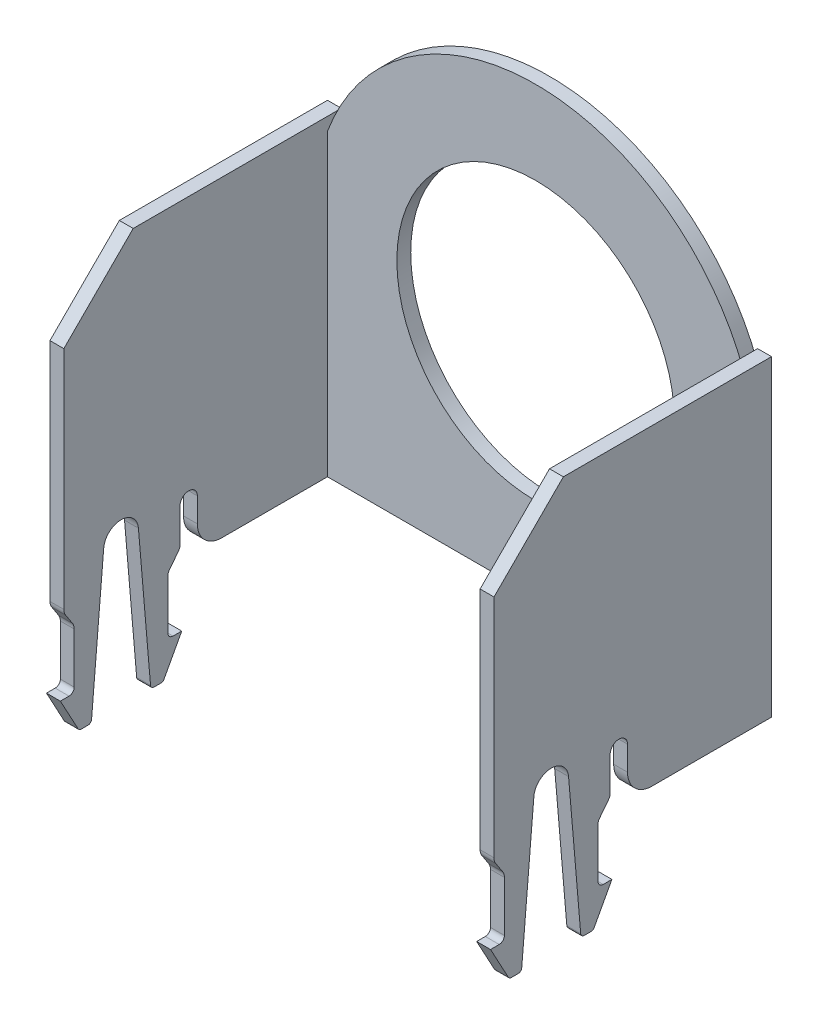
SolidWorks part; units mm, degrees
ref_plane "Płaszczyzna przednia" through (0, 0, 0) normal (0, 0, 1) x (1, 0, 0)
ref_plane "Płaszczyzna górna" through (0, 0, 0) normal (0, 1, 0) x (1, 0, 0)
ref_plane "Płaszczyzna prawa" through (0, 0, 0) normal (1, 0, 0) x (0, 0, -1)
sketch "Szkic1" plane through (0, 0, 0) normal (0, 0, 1) x (1, 0, 0)
  line L0 (0, -6.4) -> (6.4, -6.4)
  line L1 (6.4, -6.4) -> (6.4, 0)
  line L2 (-6.4, 0) -> (-6.4, -6.4)
  line L3 (-6.4, -6.4) -> (0, -6.4)
  arc A0 (6.4, 0) -> (-6.4, 0) centre (0, 0) ccw
  dimension "D1" = 12.8
extrude "Dodanie-wyciągnięcie1" add sketch "Szkic1" along normal blind 0.4
sketch "Szkic6" plane through (0, 0, 0.4) normal (0, 0, 1) x (1, 0, 0)
  circle A0 centre (0, 0) radius 4
  dimension "D1" = 8
extrude "Wytnij-wyciągnięcie1" cut sketch "Szkic6" against normal up to next
ref_plane "Płaszczyzna1" through (0, 0, 0) normal (1, 0, 0) x (0, 0, -1)
sketch "Szkic5" plane through (-6.4, 0, 0) normal (-1, 0, 0) x (0, 0, 1)
  line L0 (5.0007, -6.5686) -> (5.0007, -8)
  line L2 (4.8507, -8.15) -> (4.6007, -8.15)
  line L3 (4.6007, -8.15) -> (5.1127, -9.0975)
  line L4 (5.2007, -9.15) -> (5.4007, -9.15)
  line L5 (5.5004, -9.0585) -> (5.8504, -4.9573)
  line L6 (247.5333, 468.0971) -> (1270.2, 468.0971) construction
  line L7 (6.8504, -4.9573) -> (7.2004, -9.0585)
  line L8 (7.3, -9.15) -> (7.5, -9.15)
  line L9 (7.588, -9.0975) -> (8.1, -8.15)
  line L10 (8.1, -8.15) -> (7.85, -8.15)
  line L12 (4.6929, -6.1042) -> (4.9586, -6.4458)
  line L14 (4.1507, -5.7) -> (4.1507, -5)
  line L15 (233.389, 400.0695) -> (1256.0557, 400.0695) construction
  line L16 (4.6507, -5) -> (4.6507, -5.9814)
  line L17 (7.7, -8) -> (7.7, -6.55)
  line L18 (8, -5.911) -> (8, 0.6)
  line L19 (6, 2.6) -> (0, 2.6)
  line L20 (0, 2.6) -> (0, -6.4)
  line L21 (0, -6.4) -> (3.4507, -6.4)
  line L23 (7.7486, -6.3864) -> (7.9514, -6.0746)
  line L24 (6, 2.6) -> (8, 0.6)
  arc A0 (4.6507, -5) -> (4.1507, -5) centre (4.4007, -5) ccw
  arc A1 (4.1507, -5.7) -> (3.4507, -6.4) centre (3.4507, -5.7) cw
  arc A4 (5.0007, -8) -> (4.8507, -8.15) centre (4.8507, -8) cw
  arc A5 (5.4007, -9.15) -> (5.5004, -9.0585) centre (5.4007, -9.05) ccw
  arc A6 (5.1127, -9.0975) -> (5.2007, -9.15) centre (5.2007, -9.05) ccw
  arc A7 (6.8504, -4.9573) -> (5.8504, -4.9573) centre (6.3504, -5) ccw
  arc A8 (7.5, -9.15) -> (7.588, -9.0975) centre (7.5, -9.05) ccw
  arc A9 (7.2004, -9.0585) -> (7.3, -9.15) centre (7.3, -9.05) ccw
  arc A10 (7.85, -8.15) -> (7.7, -8) centre (7.85, -8) cw
  arc A13 (5.0007, -6.5686) -> (4.9586, -6.4458) centre (4.8007, -6.5686) ccw
  arc A14 (4.6929, -6.1042) -> (4.6507, -5.9814) centre (4.8507, -5.9814) cw
  arc A15 (8, -5.911) -> (7.9514, -6.0746) centre (7.7, -5.911) cw
  arc A16 (7.7, -6.55) -> (7.7486, -6.3864) centre (8, -6.55) cw
  point P30 (5.0007, -6.5)
  point P32 (8, -6)
  point P37 (5.0007, -8.15)
  point P42 (5.1411, -9.15)
  point P53 (8, -6.55)
  point P57 (8, 0.6)
  point P61 (4.6507, -6.05)
  point P64 (6, 2.6)
  dimension "D4" = 2
  dimension "D6" = 0.35
  dimension "D12" = 0.15
  dimension "D13" = 0.1
  dimension "D18" = 0.1
  dimension "D22" = 0.15
  dimension "D7" = 0.7
  dimension "D15" = 9
  dimension "D28" = 0.2
  dimension "D32" = 0.3
  dimension "D29" = 0.2
  dimension "D2" = 0.5
  dimension "D3" = 0.35
  dimension "D5" = 0.7
  dimension "D8" = 0.4
  dimension "D9" = 1.4
  dimension "D10" = 0.4
  dimension "D11" = 1
  dimension "D14" = 0.6
  dimension "D17" = 0.6
  dimension "D19" = 1
  dimension "D20" = 0.2
  dimension "D21" = 1.4
  dimension "D23" = 0.3
  dimension "D24" = 0.35
  dimension "D25" = 0.1
  dimension "D26" = 0.35
  dimension "D27" = 1.75
  dimension "D30" = 6
  dimension "0," = 0.4
  dimension "D33" = 0.15
  dimension "D34" = 2
extrude "Dodanie-wyciągnięcie4" add sketch "Szkic5" against normal blind 0.4
mirror "Lustro1" about plane through (0, 0, 0) normal (1, 0, 0) of "Dodanie-wyciągnięcie4"
